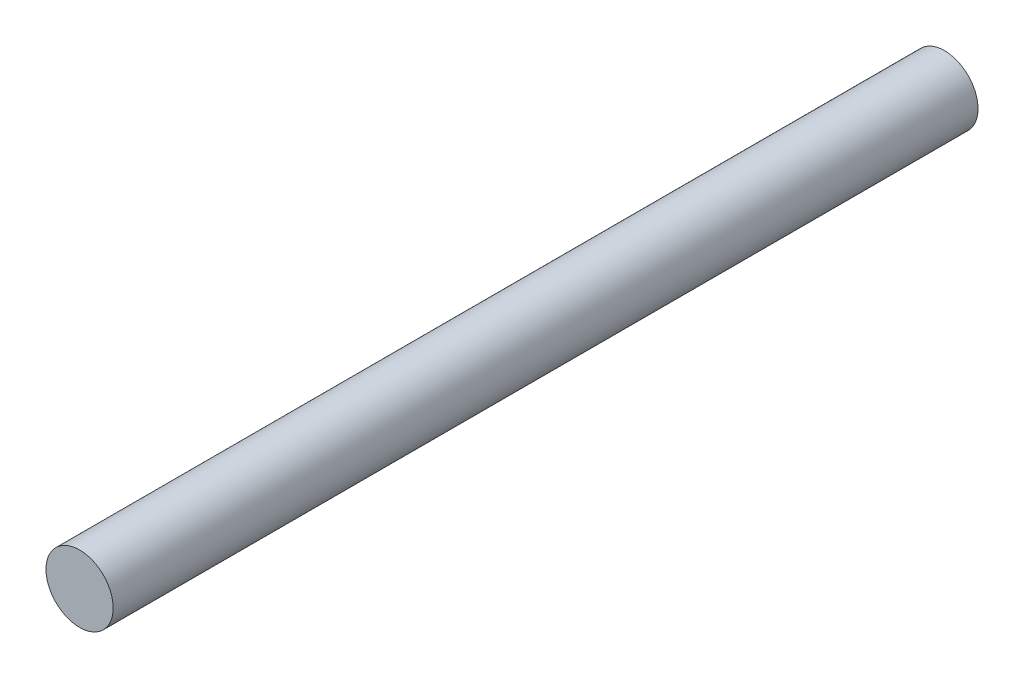
SolidWorks part; units mm, degrees
ref_plane "前视基准面" through (0, 0, 0) normal (0, 0, 1) x (1, 0, 0)
ref_plane "上视基准面" through (0, 0, 0) normal (0, 1, 0) x (1, 0, 0)
ref_plane "右视基准面" through (0, 0, 0) normal (1, 0, 0) x (0, 0, -1)
sketch "草图1" plane through (0, 0, 0) normal (0, 0, 1) x (1, 0, 0)
  circle A1 centre (0, 0) radius 0.8
  dimension "D1" = 1.6
extrude "凸台-拉伸1" add sketch "草图1" along normal blind 20.6
